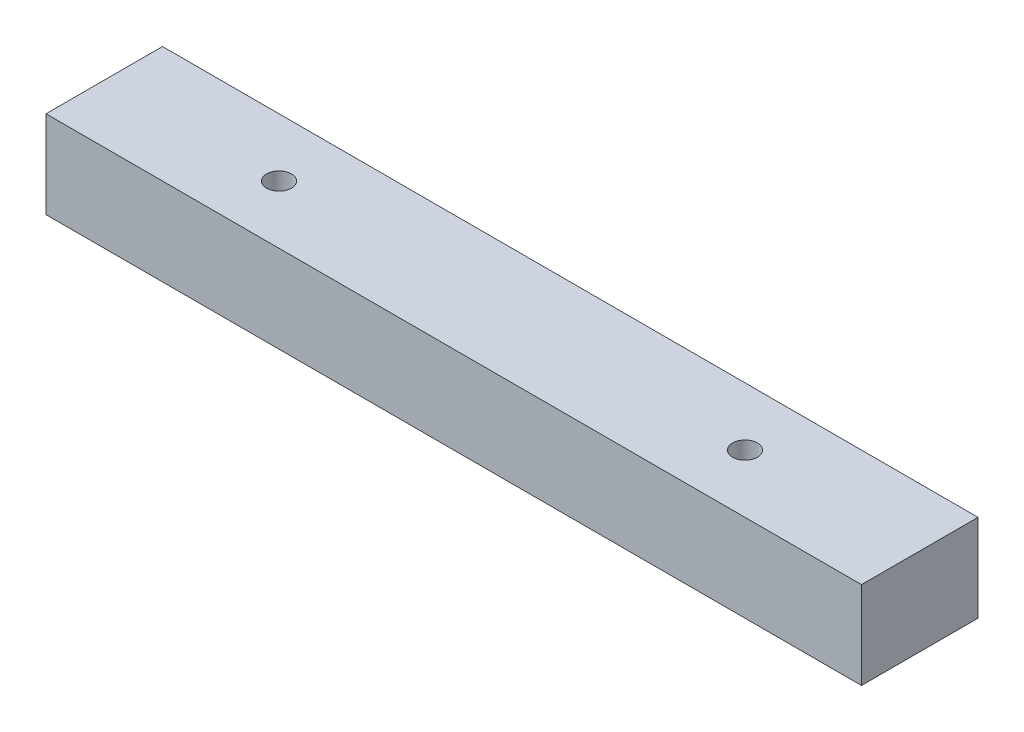
SolidWorks part; units mm, degrees
material "6061 Alloy"
ref_plane "Front Plane" through (0, 0, 0) normal (0, 0, 1) x (1, 0, 0)
ref_plane "Top Plane" through (0, 0, 0) normal (0, 1, 0) x (1, 0, 0)
ref_plane "Right Plane" through (0, 0, 0) normal (1, 0, 0) x (0, 0, -1)
sketch "Sketch1" plane through (0, 0, 0) normal (0, 1, 0) x (1, 0, 0)
  line L1 (44.45, -6.35) -> (-44.45, -6.35)
  line L2 (44.45, -6.35) -> (44.45, 6.35)
  line L3 (44.45, 6.35) -> (-44.45, 6.35)
  line L4 (-44.45, -6.35) -> (-44.45, 6.35)
  line L5 (44.45, -6.35) -> (-44.45, 6.35) construction
  line L6 (44.45, 6.35) -> (-44.45, -6.35) construction
  point P0 (0, 0)
  dimension "D1" = 88.9
  dimension "D2" = 12.7
extrude "Boss-Extrude1" add sketch "Sketch1" along normal blind 9.525
hole_wizard "#6-32 Tapped Hole1" positions "Sketch3" profile "Sketch2" tap size "#6-32" standard "Ansi Inch" end condition through all
sketch "Sketch3" plane through (0, 0, 0) normal (0, -1, 0) x (1, 0, 0)
  point P1 (25.4, 0)
  point P4 (-25.4, 0)
  dimension "D1" = 25.4
  dimension "D2" = 50.8
sketch "Sketch2" plane through (25.4, 0, 0) normal (1, 0, 0) x (0, 0, -1)
  line L0 (0, 0) -> (0, 9.525)
  line L1 (0, 9.525) -> (1.3525, 9.525)
  line L2 (1.3525, 9.525) -> (1.3525, 0)
  line L5 (1.3525, 0) -> (0, 0)
  line L11 (0, -6.35) -> (0, 107.95) construction
  dimension "Thru Tap Drill Dia." = 2.7051
  dimension "Thru Tap Drill Depth" = 9.525
cosmetic thread "Hole Thread1" parameters "D2"=3.5052
cosmetic thread "Hole Thread2" parameters "D2"=3.5052
equation "\"D1@Sketch3\" = \"D2@Sketch3\"/2"
